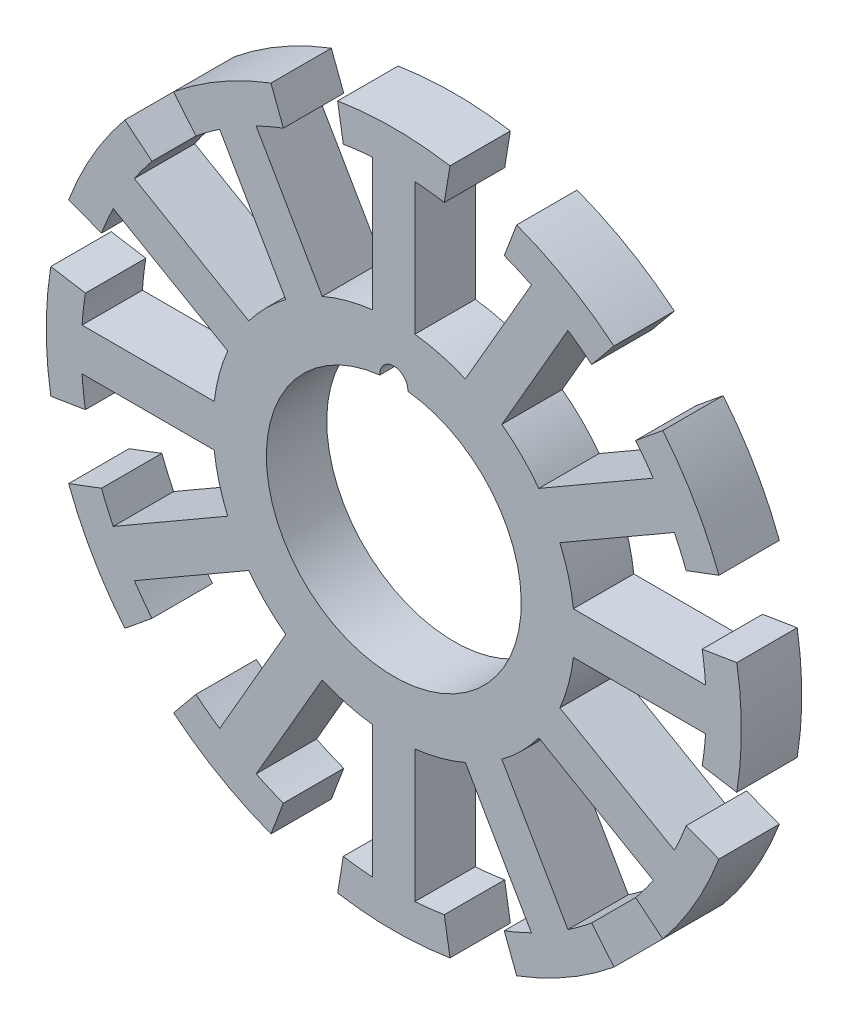
SolidWorks part; units mm, degrees
ref_plane "Front Plane" through (0, 0, 0) normal (0, 0, 1) x (1, 0, 0)
ref_plane "Top Plane" through (0, 0, 0) normal (0, 1, 0) x (1, 0, 0)
ref_plane "Right Plane" through (0, 0, 0) normal (1, 0, 0) x (0, 0, -1)
sketch "Sketch1" plane through (0, 0, 0) normal (0, 0, 1) x (1, 0, 0)
  circle A0 centre (0, 0) radius 12.573
extrude "Extrude1" add sketch "Sketch1" along normal blind 2.1844
sketch "Sketch2" plane through (0, 0, 2.1844) normal (0, 0, 1) x (1, 0, 0)
  line L0 (3.9952, 10.5734) -> (4.4441, 11.7614)
  line L1 (0.762, 6.496) -> (0.762, 11.2773)
  line L2 (-0.762, 6.496) -> (-0.762, 11.2773)
  line L4 (2.5881, 6.0067) -> (4.9787, 10.1474)
  line L5 (-1.8267, 11.1544) -> (-2.032, 12.4077)
  line L6 (1.8267, 11.1544) -> (2.032, 12.4077)
  line L7 (3.9079, 5.2447) -> (6.2986, 9.3854)
  line L8 (7.1592, 8.7466) -> (7.9636, 9.7294)
  line L9 (8.7466, 7.1592) -> (9.7294, 7.9636)
  line L10 (5.2447, 3.9079) -> (9.3854, 6.2986)
  line L11 (6.0067, 2.5881) -> (10.1474, 4.9787)
  line L12 (10.5734, 3.9952) -> (11.7614, 4.4441)
  line L13 (11.1544, 1.8267) -> (12.4077, 2.032)
  line L14 (6.496, 0.762) -> (11.2773, 0.762)
  line L15 (6.496, -0.762) -> (11.2773, -0.762)
  line L16 (11.1544, -1.8267) -> (12.4077, -2.032)
  line L17 (10.5734, -3.9952) -> (11.7614, -4.4441)
  line L18 (6.0067, -2.5881) -> (10.1474, -4.9787)
  line L19 (5.2447, -3.9079) -> (9.3854, -6.2986)
  line L20 (8.7466, -7.1592) -> (9.7294, -7.9636)
  line L21 (7.1592, -8.7466) -> (7.9636, -9.7294)
  line L22 (3.9079, -5.2447) -> (6.2986, -9.3854)
  line L23 (2.5881, -6.0067) -> (4.9787, -10.1474)
  line L24 (3.9952, -10.5734) -> (4.4441, -11.7614)
  line L25 (1.8267, -11.1544) -> (2.032, -12.4077)
  line L26 (0.762, -6.496) -> (0.762, -11.2773)
  line L27 (-0.762, -6.496) -> (-0.762, -11.2773)
  line L28 (-1.8267, -11.1544) -> (-2.032, -12.4077)
  line L29 (-3.9952, -10.5734) -> (-4.4441, -11.7614)
  line L30 (-2.5881, -6.0067) -> (-4.9787, -10.1474)
  line L31 (-3.9079, -5.2447) -> (-6.2986, -9.3854)
  line L32 (-7.1592, -8.7466) -> (-7.9636, -9.7294)
  line L33 (-8.7466, -7.1592) -> (-9.7294, -7.9636)
  line L34 (-5.2447, -3.9079) -> (-9.3854, -6.2986)
  line L35 (-6.0067, -2.5881) -> (-10.1474, -4.9787)
  line L36 (-10.5734, -3.9952) -> (-11.7614, -4.4441)
  line L37 (-11.1544, -1.8267) -> (-12.4077, -2.032)
  line L38 (-6.496, -0.762) -> (-11.2773, -0.762)
  line L39 (-6.496, 0.762) -> (-11.2773, 0.762)
  line L40 (-11.1544, 1.8267) -> (-12.4077, 2.032)
  line L41 (-10.5734, 3.9952) -> (-11.7614, 4.4441)
  line L42 (-6.0067, 2.5881) -> (-10.1474, 4.9787)
  line L43 (-5.2447, 3.9079) -> (-9.3854, 6.2986)
  line L44 (-8.7466, 7.1592) -> (-9.7294, 7.9636)
  line L45 (-7.1592, 8.7466) -> (-7.9636, 9.7294)
  line L46 (-3.9079, 5.2447) -> (-6.2986, 9.3854)
  line L47 (-2.5881, 6.0067) -> (-4.9787, 10.1474)
  line L48 (-3.9952, 10.5734) -> (-4.4441, 11.7614)
  arc A0 (-0.762, 6.496) -> (-2.5881, 6.0067) centre (0, 0) ccw
  arc A1 (1.8267, 11.1544) -> (0.762, 11.2773) centre (0, 0) ccw
  circle A3 centre (0, 0) radius 12.573 construction
  arc A4 (-0.762, 11.2773) -> (-1.8267, 11.1544) centre (0, 0) ccw
  arc A5 (4.9787, 10.1474) -> (3.9952, 10.5734) centre (0, 0) ccw
  arc A6 (7.1592, 8.7466) -> (6.2986, 9.3854) centre (0, 0) ccw
  arc A7 (9.3854, 6.2986) -> (8.7466, 7.1592) centre (0, 0) ccw
  arc A8 (10.5734, 3.9952) -> (10.1474, 4.9787) centre (0, 0) ccw
  arc A9 (11.2773, 0.762) -> (11.1544, 1.8267) centre (0, 0) ccw
  arc A10 (11.1544, -1.8267) -> (11.2773, -0.762) centre (0, 0) ccw
  arc A11 (10.1474, -4.9787) -> (10.5734, -3.9952) centre (0, 0) ccw
  arc A12 (8.7466, -7.1592) -> (9.3854, -6.2986) centre (0, 0) ccw
  arc A13 (6.2986, -9.3854) -> (7.1592, -8.7466) centre (0, 0) ccw
  arc A14 (3.9952, -10.5734) -> (4.9787, -10.1474) centre (0, 0) ccw
  arc A15 (0.762, -11.2773) -> (1.8267, -11.1544) centre (0, 0) ccw
  arc A16 (-1.8267, -11.1544) -> (-0.762, -11.2773) centre (0, 0) ccw
  arc A17 (-4.9787, -10.1474) -> (-3.9952, -10.5734) centre (0, 0) ccw
  arc A18 (-7.1592, -8.7466) -> (-6.2986, -9.3854) centre (0, 0) ccw
  arc A19 (-9.3854, -6.2986) -> (-8.7466, -7.1592) centre (0, 0) ccw
  arc A20 (-10.5734, -3.9952) -> (-10.1474, -4.9787) centre (0, 0) ccw
  arc A21 (-11.2773, -0.762) -> (-11.1544, -1.8267) centre (0, 0) ccw
  arc A22 (-11.1544, 1.8267) -> (-11.2773, 0.762) centre (0, 0) ccw
  arc A23 (-10.1474, 4.9787) -> (-10.5734, 3.9952) centre (0, 0) ccw
  arc A24 (-8.7466, 7.1592) -> (-9.3854, 6.2986) centre (0, 0) ccw
  arc A25 (-6.2986, 9.3854) -> (-7.1592, 8.7466) centre (0, 0) ccw
  arc A26 (-3.9952, 10.5734) -> (-4.9787, 10.1474) centre (0, 0) ccw
  arc A27 (-3.9079, 5.2447) -> (-5.2447, 3.9079) centre (0, 0) ccw
  arc A28 (-6.0067, 2.5881) -> (-6.496, 0.762) centre (0, 0) ccw
  arc A29 (-6.496, -0.762) -> (-6.0067, -2.5881) centre (0, 0) ccw
  arc A30 (-5.2447, -3.9079) -> (-3.9079, -5.2447) centre (0, 0) ccw
  arc A31 (-2.5881, -6.0067) -> (-0.762, -6.496) centre (0, 0) ccw
  arc A32 (0.762, -6.496) -> (2.5881, -6.0067) centre (0, 0) ccw
  arc A33 (3.9079, -5.2447) -> (5.2447, -3.9079) centre (0, 0) ccw
  arc A34 (6.0067, -2.5881) -> (6.496, -0.762) centre (0, 0) ccw
  arc A35 (6.496, 0.762) -> (6.0067, 2.5881) centre (0, 0) ccw
  arc A36 (5.2447, 3.9079) -> (3.9079, 5.2447) centre (0, 0) ccw
  arc A37 (2.5881, 6.0067) -> (0.762, 6.496) centre (0, 0) ccw
  circle M1 centre (0, 0) radius 12.573
extrude "Cut-Extrude1" cut sketch "Sketch2" against normal through all contours A27 L46 A25 L45 L44 A24 L43 M1 | A28 L42 A23 L41 L40 A22 L39 M1 | A29 L38 A21 L37 L36 A20 L35 M1 | A30 L34 A19 L33 L32 A18 L31 M1 | A31 L30 A17 L29 L28 A16 L27 M1 | A32 L26 A15 L25 L24 A14 L23 M1 | A33 L22 A13 L21 L20 A12 L19 M1 | A34 L18 A11 L17 L16 A10 L15 M1 | A35 L14 A9 L13 L12 A8 L11 M1 | A36 L10 A7 L9 L8 A6 L7 M1 | A37 L4 A5 L0 L6 A1 L1 M1 | L48 A26 L47 A0 L2 A4 L5 M1
sketch "Sketch4" plane through (0, 0, 2.1844) normal (0, 0, 1) x (1, 0, 0)
  circle A0 centre (0, 0) radius 4.6101
extrude "Cut-Extrude2" cut sketch "Sketch4" against normal through all
sketch "Sketch5" plane through (0, 0, 2.1844) normal (0, 0, 1) x (1, 0, 0)
  circle A0 centre (0, 4.6101) radius 0.508
extrude "Cut-Extrude3" cut sketch "Sketch5" against normal through all
